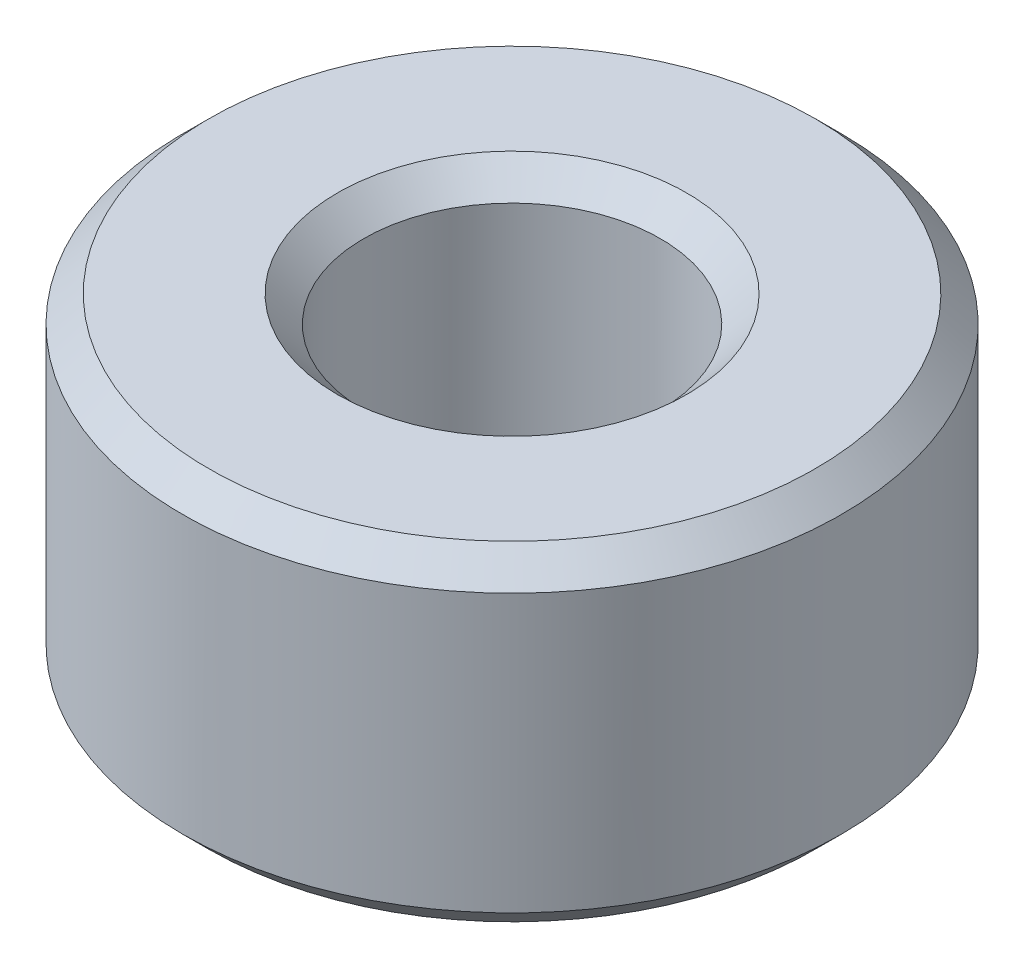
SolidWorks part; units mm, degrees
material "PET"
ref_plane "Front Plane" through (0, 0, 0) normal (0, 0, 1) x (1, 0, 0)
ref_plane "Top Plane" through (0, 0, 0) normal (0, 1, 0) x (1, 0, 0)
ref_plane "Right Plane" through (0, 0, 0) normal (1, 0, 0) x (0, 0, -1)
sketch "body_sketch" plane through (0, 0, 0) normal (0, 1, 0) x (1, 0, 0)
  circle A0 centre (0, 0) radius 5
  circle A1 centre (0, 0) radius 2.25
  dimension "D1" = 4.5
  dimension "D2" = 10
extrude "body" add sketch "body_sketch" along normal blind 5
chamfer "chamfers" distance 0.4 angle 45 4 edges at (0, 0, 5) (0, 0, 2.25) (0, 5, 5) (0, 5, 2.25)
